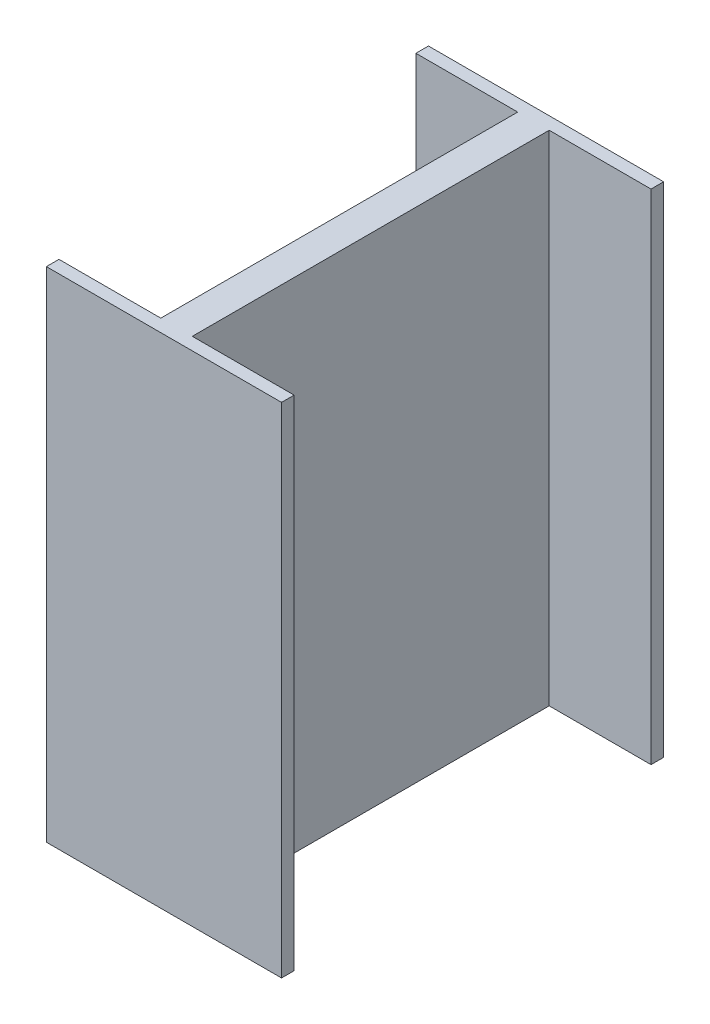
SolidWorks part; units mm, degrees
material "Payload"
ref_plane "Front Plane" through (0, 0, 0) normal (0, 0, 1) x (1, 0, 0)
ref_plane "Top Plane" through (0, 0, 0) normal (0, 1, 0) x (1, 0, 0)
ref_plane "Right Plane" through (0, 0, 0) normal (1, 0, 0) x (0, 0, -1)
sketch "Sketch1" plane through (0, 0, 0) normal (0, 1, 0) x (1, 0, 0)
  line L0 (-616.0327, 0) -> (616.0327, 0) construction
  line L1 (560.0298, 0) -> (280.0149, 485)
  line L2 (280.0149, 485) -> (-280.0149, 485)
  line L3 (-280.0149, 485) -> (-560.0298, 0)
  line L4 (-560.0298, 0) -> (-280.0149, -485)
  line L5 (-280.0149, -485) -> (280.0149, -485)
  line L6 (280.0149, -485) -> (560.0298, 0)
  line L7 (-37.5, 455) -> (37.5, 455)
  line L8 (-37.5, 425) -> (-37.5, -425)
  line L9 (-37.5, -455) -> (37.5, -455)
  line L10 (37.5, 425) -> (37.5, -425)
  line L11 (-37.5, 455) -> (37.5, -455) construction
  line L12 (-37.5, -455) -> (37.5, 455) construction
  line L13 (37.5, 455) -> (280.0149, 455)
  line L15 (37.5, 425) -> (280.0149, 425)
  line L16 (280.0149, 455) -> (280.0149, 425)
  line L17 (280.0149, -455) -> (280.0149, -425)
  line L18 (37.5, -455) -> (280.0149, -455)
  line L19 (37.5, -425) -> (280.0149, -425)
  line L20 (0, -533.5) -> (0, 533.5) construction
  line L21 (-280.0149, -455) -> (-280.0149, -425)
  line L22 (-37.5, -455) -> (-280.0149, -455)
  line L23 (-37.5, -425) -> (-280.0149, -425)
  line L24 (-280.0149, 455) -> (-280.0149, 425)
  line L25 (-37.5, 455) -> (-280.0149, 455)
  line L26 (-37.5, 425) -> (-280.0149, 425)
  circle A0 centre (0, 0) radius 485 construction
  dimension "D1" = 970
  dimension "D2" = 75
  dimension "D3" = 30
  dimension "D4" = 30
  dimension "D5" = 75
extrude "Boss-Extrude2" add sketch "Sketch1" along normal blind 1187.25 contours L8 L23 L21 L22 L9 L18 L17 L19 L10 L15 L16 L13 L7 L25 L24 L26
